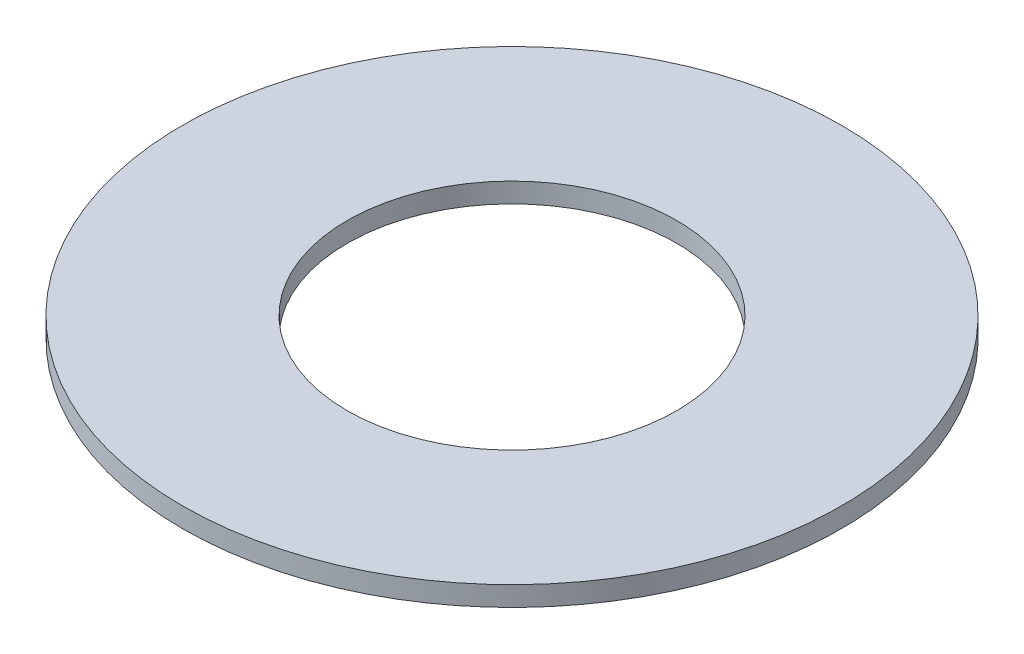
SolidWorks part; units mm, degrees
ref_plane "Front Plane" through (0, 0, 0) normal (0, 0, 1) x (1, 0, 0)
ref_plane "Top Plane" through (0, 0, 0) normal (0, 1, 0) x (1, 0, 0)
ref_plane "Right Plane" through (0, 0, 0) normal (1, 0, 0) x (0, 0, -1)
sketch "Sketch1" plane through (0, 0, 0) normal (1, 0, 0) x (0, 0, -1)
  line L0 (0, 14.2862) -> (0, -22.3775) construction
  line L1 (3.175, 0) -> (0, 0) construction
  line L2 (3.175, 0.1905) -> (6.35, 0.1905)
  line L3 (3.175, 0.1905) -> (3.175, -0.1905)
  line L4 (3.175, -0.1905) -> (6.35, -0.1905)
  line L5 (6.35, 0.1905) -> (6.35, -0.1905)
  dimension "ID" = 6.35
  dimension "OD" = 12.7
  dimension "T" = 0.381
revolve "Revolve1" add sketch "Sketch1" angle 360 about L0
